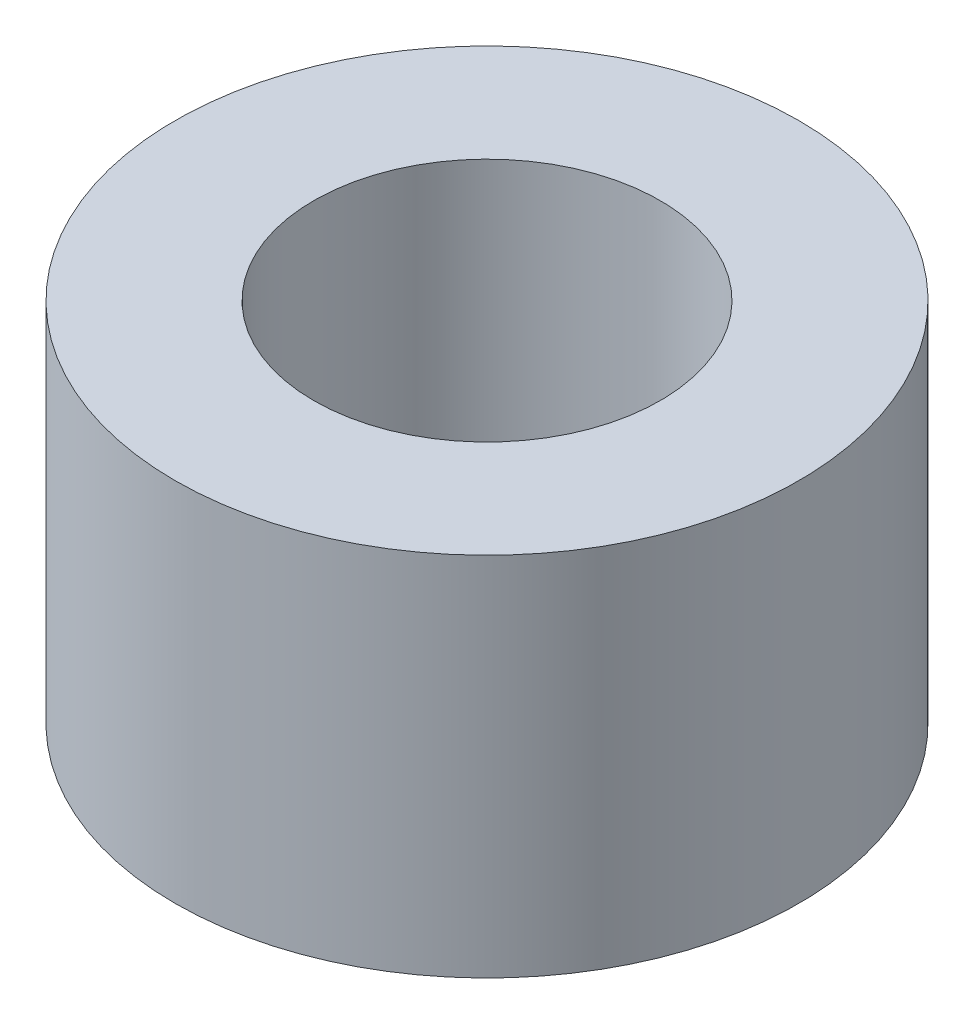
SolidWorks part; units mm, degrees
ref_plane "Front Plane" through (0, 0, 0) normal (0, 0, 1) x (1, 0, 0)
ref_plane "Top Plane" through (0, 0, 0) normal (0, 1, 0) x (1, 0, 0)
ref_plane "Right Plane" through (0, 0, 0) normal (1, 0, 0) x (0, 0, -1)
sketch "Sketch1" plane through (0, 0, 0) normal (0, 1, 0) x (1, 0, 0)
  circle A0 centre (0, 0) radius 3
  circle A1 centre (0, 0) radius 5.4
  dimension "D1" = 6
  dimension "D2" = 10.8
extrude "Boss-Extrude1" add sketch "Sketch1" along normal blind 6.34
